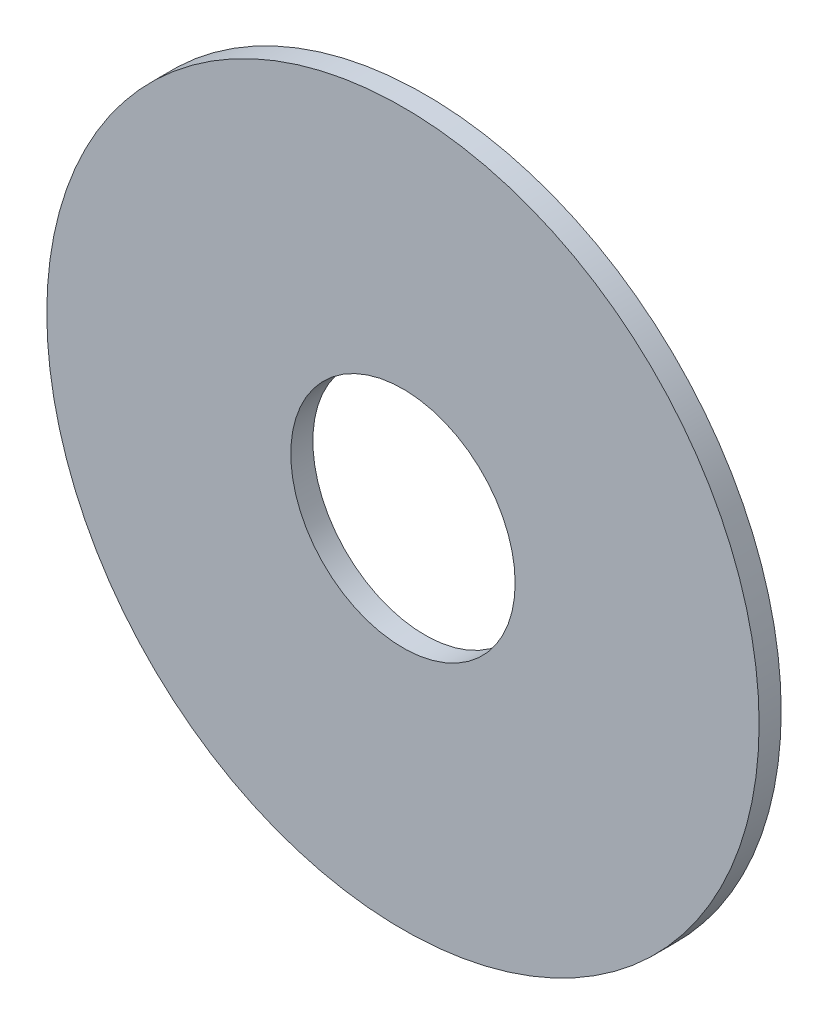
SolidWorks part; units mm, degrees
ref_plane "Front"
ref_plane "Top" through (0, 0, 0) normal (0, 1, 0) x (1, 0, 0)
ref_plane "Right" through (0, 0, 0) normal (1, 0, 0) x (0, 0, -1)
sketch "Sketch1" plane through (0, 0, 0) normal (0, 0, 1) x (1, 0, 0)
  circle A0 centre (0, 0) radius 4.0005
  circle A1 centre (0, 0) radius 12.7
  dimension "D1" = 8.001
  dimension "D2" = 25.4
extrude "Extrude1" add sketch "Sketch1" along normal blind 0.7874 contours A1 A0
